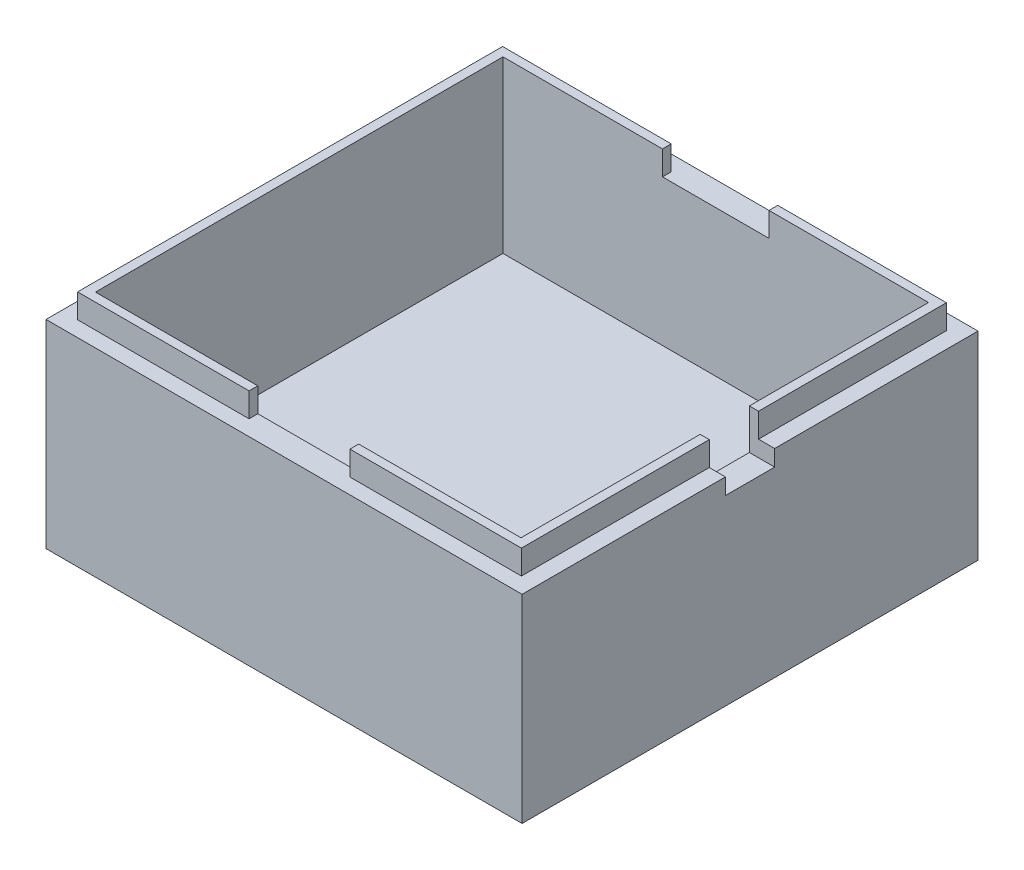
SolidWorks part; units mm, degrees
ref_plane "Front Plane" through (0, 0, 0) normal (0, 0, 1) x (1, 0, 0)
ref_plane "Top Plane" through (0, 0, 0) normal (0, 1, 0) x (1, 0, 0)
ref_plane "Right Plane" through (0, 0, 0) normal (1, 0, 0) x (0, 0, -1)
sketch "Sketch1" plane through (0, 0, 0) normal (0, 1, 0) x (1, 0, 0)
  line L1 (-29.5, -28.25) -> (29.5, -28.25)
  line L2 (-29.5, -28.25) -> (-29.5, 28.25)
  line L3 (-29.5, 28.25) -> (29.5, 28.25)
  line L4 (29.5, -28.25) -> (29.5, 28.25)
  line L5 (-29.5, -28.25) -> (29.5, 28.25) construction
  line L6 (-29.5, 28.25) -> (29.5, -28.25) construction
  point P0 (0, 0)
  dimension "D1" = 59
  dimension "D2" = 56.5
extrude "Boss-Extrude1" add sketch "Sketch1" along normal blind 6.5
sketch "Sketch5" plane through (0, 6.5, 0) normal (0, 1, 0) x (1, 0, 0)
  line L1 (-29.5, -28.25) -> (29.5, -28.25)
  line L2 (-29.5, -28.25) -> (-29.5, 28.25)
  line L3 (-29.5, 28.25) -> (29.5, 28.25)
  line L4 (29.5, -28.25) -> (29.5, 28.25)
  line L5 (-29.5, -28.25) -> (29.5, 28.25) construction
  line L6 (-29.5, 28.25) -> (29.5, -28.25) construction
  line L7 (-26.3673, -25.25) -> (26.3673, -25.25)
  line L8 (-26.3673, -25.25) -> (-26.3673, 25.25)
  line L9 (-26.3673, 25.25) -> (26.3673, 25.25)
  line L10 (26.3673, -25.25) -> (26.3673, 25.25)
  line L11 (-26.3673, -25.25) -> (26.3673, 25.25) construction
  line L12 (-26.3673, 25.25) -> (26.3673, -25.25) construction
  point P0 (0, 0)
  point P7 (0, 0)
  dimension "D1" = 3
extrude "Boss-Extrude2" add sketch "Sketch5" along normal blind 21.1
sketch "Sketch6" plane through (0, 27.6, 0) normal (0, 1, 0) x (1, 0, 0)
  line L1 (-29.5, -28.25) -> (29.5, -28.25)
  line L2 (-29.5, -28.25) -> (-29.5, 28.25)
  line L3 (-29.5, 28.25) -> (29.5, 28.25)
  line L4 (29.5, -28.25) -> (29.5, 28.25)
  line L5 (-29.5, -28.25) -> (29.5, 28.25) construction
  line L6 (-29.5, 28.25) -> (29.5, -28.25) construction
  line L7 (-27.5, -26.3347) -> (27.5, -26.3347)
  line L8 (-27.5, -26.3347) -> (-27.5, 26.3347)
  line L9 (-27.5, 26.3347) -> (27.5, 26.3347)
  line L10 (27.5, -26.3347) -> (27.5, 26.3347)
  line L11 (-27.5, -26.3347) -> (27.5, 26.3347) construction
  line L12 (-27.5, 26.3347) -> (27.5, -26.3347) construction
  point P0 (0, 0)
  point P7 (0, 0)
  dimension "D1" = 2
extrude "Cut-Extrude2" cut sketch "Sketch6" against normal blind 3
sketch "Sketch7" plane through (0, 27.6, 0) normal (0, 1, 0) x (1, 0, 0)
  line L0 (0, 26.3347) -> (0, -26.3347) construction
  line L1 (27.5, 26.3347) -> (-27.5, 26.3347) construction
  line L2 (-27.5, -26.3347) -> (27.5, -26.3347) construction
  line L4 (-26.3673, -25.25) -> (26.3673, -25.25) construction
  line L5 (-6.25, -27.4195) -> (6.25, -27.4195)
  line L6 (-6.25, -27.4195) -> (-6.25, -25.25)
  line L7 (-6.25, -25.25) -> (6.25, -25.25)
  line L8 (6.25, -27.4195) -> (6.25, -25.25)
  line L9 (-6.25, -27.4195) -> (6.25, -25.25) construction
  line L10 (-6.25, -25.25) -> (6.25, -27.4195) construction
  line L11 (29.5, 28.25) -> (-29.5, 28.25) construction
  line L12 (-6.6, 24.4195) -> (6.6, 24.4195)
  line L13 (-6.6, 24.4195) -> (-6.6, 28.25)
  line L14 (-6.6, 28.25) -> (6.6, 28.25)
  line L15 (6.6, 24.4195) -> (6.6, 28.25)
  line L16 (-6.6, 24.4195) -> (6.6, 28.25) construction
  line L17 (-6.6, 28.25) -> (6.6, 24.4195) construction
  line L18 (26.3673, -25.25) -> (26.3673, 25.25) construction
  line L19 (25.2345, -3.05) -> (27.5, -3.05)
  line L20 (25.2345, -3.05) -> (25.2345, 3.05)
  line L21 (25.2345, 3.05) -> (27.5, 3.05)
  line L22 (27.5, -3.05) -> (27.5, 3.05)
  line L23 (25.2345, -3.05) -> (27.5, 3.05) construction
  line L24 (25.2345, 3.05) -> (27.5, -3.05) construction
  line L25 (27.5, -26.3347) -> (27.5, 26.3347) construction
  line L26 (29.5, -28.25) -> (29.5, 28.25) construction
  point P20 (26.3673, 0)
  dimension "D1" = 29.5
  dimension "D2" = 12.5
  dimension "D3" = 13.2
  dimension "D4" = 6.1
extrude "Cut-Extrude3" cut sketch "Sketch7" against normal blind 3
sketch "Sketch9" plane through (0, 24.6, 0) normal (0, 1, 0) x (1, 0, 0)
  line L0 (29.5, -28.25) -> (29.5, 28.25) construction
  line L1 (26.3673, -3.05) -> (29.5, -3.05)
  line L2 (26.3673, -3.05) -> (26.3673, 3.05)
  line L3 (26.3673, 3.05) -> (29.5, 3.05)
  line L4 (29.5, -3.05) -> (29.5, 3.05)
  line L5 (26.3673, -25.25) -> (26.3673, 25.25) construction
  point P8 (26.3673, 0)
  dimension "D1" = 6.1
extrude "Cut-Extrude5" cut sketch "Sketch9" against normal blind 2
sketch "Sketch11" plane through (0, 0, 0) normal (0, -1, 0) x (-1, 0, 0)
  line L0 (-29.5, 28.25) -> (29.5, 28.25) construction
  line L1 (-29.5, -28.25) -> (-29.5, 28.25) construction
  line L2 (0, 27.3253) -> (0, -27.6747) construction
  line L3 (29.5, -28.25) -> (-29.5, -28.25) construction
  line L4 (-42.5612, 0) -> (22.4388, 0) construction
  line L5 (29.5, 28.25) -> (29.5, -28.25) construction
  circle A0 centre (-23, 21.75) radius 1.8526
  circle A1 centre (23, -21.75) radius 1.8526
  point P14 (0, 0)
  dimension "D1" = 3.7052
  dimension "D2" = 6.5
  dimension "D3" = 6.5
  dimension "D5" = 6.5
  dimension "D6" = 6.5
  dimension "D4" = 2
extrude "Cut-Extrude7" cut sketch "Sketch11" against normal blind 10
sketch "Sketch12" plane through (0, 0, 0) normal (0, -1, 0) x (1, 0, 0)
  line L0 (27.5, -3.5749) -> (27.5, -37.0919) construction
  line L1 (-27.5, 28.25) -> (-27.5, 5.1446) construction
  line L2 (-29.5, 28.25) -> (29.5, 28.25) construction
  line L3 (-29.5, -28.25) -> (-29.5, 28.25) construction
  line L4 (-29.5, 0) -> (29.5, 0) construction
  line L5 (29.5, 28.25) -> (29.5, -28.25) construction
  line L6 (0, 28.25) -> (0, -28.25) construction
  line L7 (29.5, -28.25) -> (-29.5, -28.25) construction
  circle A0 centre (-23, 21.75) radius 4.5
  circle A2 centre (23, -21.75) radius 4.5
  circle A4 centre (23, -21.75) radius 1.8526 construction
  circle A5 centre (-23, 21.75) radius 1.8526 construction
  dimension "D1" = 2
  dimension "D2" = 2
extrude "Cut-Extrude8" cut sketch "Sketch12" against normal blind 4.5
